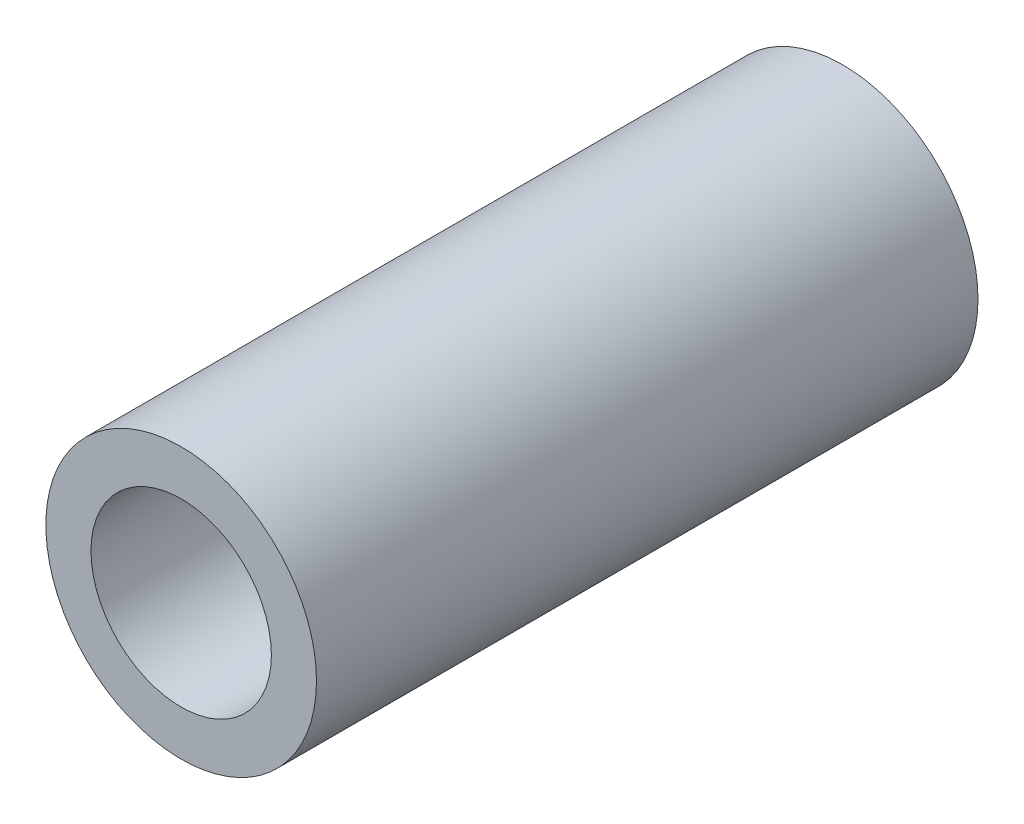
SolidWorks part; units mm, degrees
ref_plane "Alzado" through (0, 0, 0) normal (0, 0, 1) x (1, 0, 0)
ref_plane "Planta" through (0, 0, 0) normal (0, 1, 0) x (1, 0, 0)
ref_plane "Vista lateral" through (0, 0, 0) normal (1, 0, 0) x (0, 0, -1)
sketch "Croquis1" plane through (0, 0, 0) normal (0, 0, 1) x (1, 0, 0)
  circle A0 centre (0, 0) radius 4.5
  circle A1 centre (0, 0) radius 3
  dimension "D1" = 9
  dimension "D2" = 6
extrude "Saliente-Extruir1" add sketch "Croquis1" along normal blind 22
